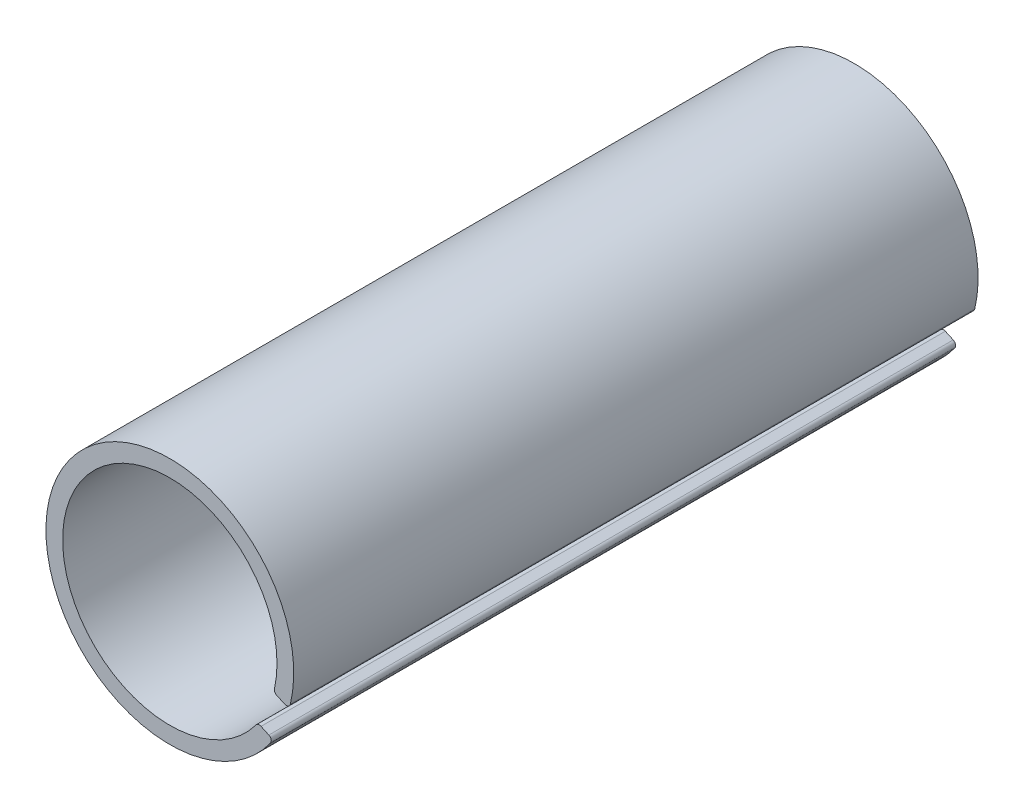
SolidWorks part; units mm, degrees
material "Chêne"
ref_plane "Plan de face" through (0, 0, 0) normal (0, 0, 1) x (1, 0, 0)
ref_plane "Plan de dessus" through (0, 0, 0) normal (0, 1, 0) x (1, 0, 0)
ref_plane "Plan de droite" through (0, 0, 0) normal (1, 0, 0) x (0, 0, -1)
sketch "Esquisse1" plane through (0, 0, 0) normal (0, 0, 1) x (1, 0, 0)
  line L3 (13.9264, -3.8067) -> (12.9737, -3.3729)
  line L4 (12.0096, -8.0124) -> (11.0568, -7.5785)
  arc A0 (12.2086, -8.7589) -> (14.6201, -3.467) centre (0, 0) cw
  arc A1 (12.0096, -8.0124) -> (12.2086, -8.7589) centre (11.8024, -8.4674) cw
  arc A2 (12.6927, -2.8098) -> (12.9737, -3.3729) centre (13.1809, -2.9178) ccw
  arc A3 (13.9264, -3.8067) -> (14.6201, -3.467) centre (14.1336, -3.3517) ccw
  arc A4 (12.6927, -2.8098) -> (10.4477, -7.736) centre (0, 0) ccw
  arc A5 (10.4477, -7.736) -> (11.0568, -7.5785) centre (10.8496, -8.0335) cw
  point P116 (0, 0)
  point P374 (0, 0)
extrude "Boss.-Extru.3" add sketch "Esquisse1" along normal blind 83
